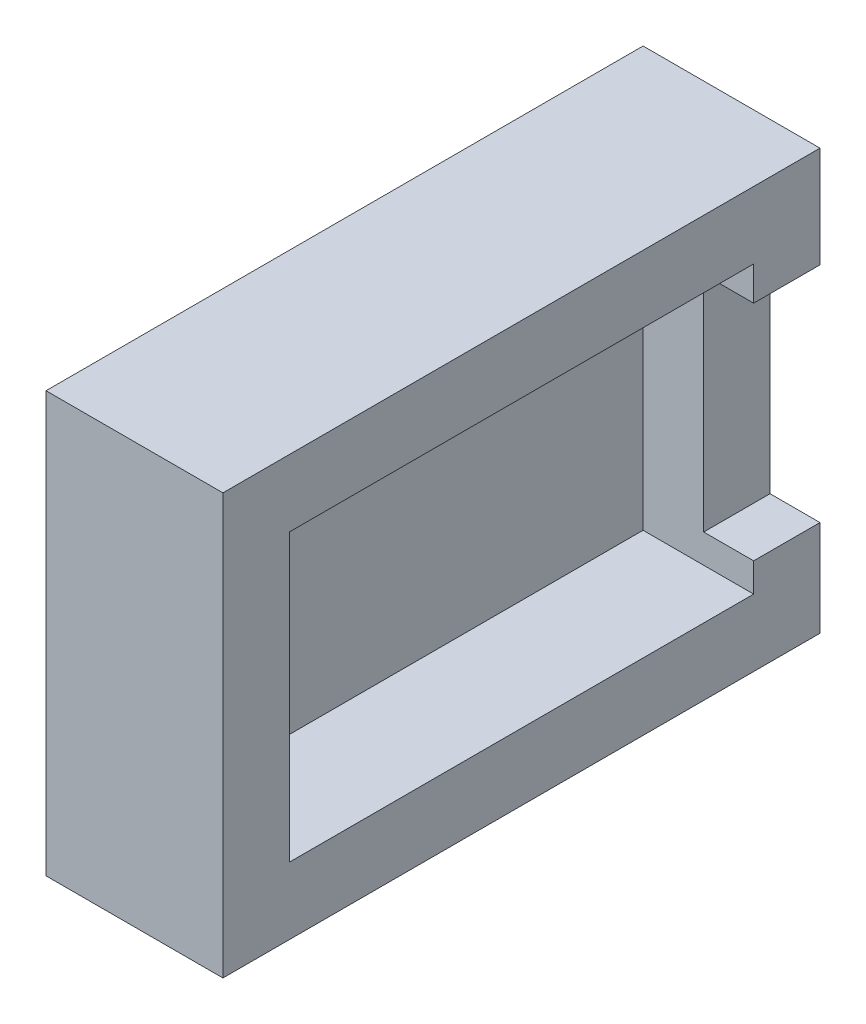
SolidWorks part; units mm, degrees
ref_plane "Front Plane" through (0, 0, 0) normal (0, 0, 1) x (1, 0, 0)
ref_plane "Top Plane" through (0, 0, 0) normal (0, 1, 0) x (1, 0, 0)
ref_plane "Right Plane" through (0, 0, 0) normal (1, 0, 0) x (0, 0, -1)
sketch "Sketch1" plane through (0, 0, 0) normal (1, 0, 0) x (0, 0, -1)
  line L1 (-13.5, 9.5) -> (13.5, 9.5)
  line L2 (-13.5, 9.5) -> (-13.5, -9.5)
  line L3 (-13.5, -9.5) -> (13.5, -9.5)
  line L4 (13.5, 9.5) -> (13.5, -9.5)
  line L5 (-13.5, 9.5) -> (13.5, -9.5) construction
  line L6 (-13.5, -9.5) -> (13.5, 9.5) construction
  point P0 (0, 0)
extrude "Boss-Extrude1" add sketch "Sketch1" along normal blind 3
sketch "Sketch2" plane through (3, 0, 0) normal (1, 0, 0) x (0, 0, -1)
  line L1 (10.5, 6.4659) -> (-10.5, 6.4659)
  line L2 (10.5, 6.4659) -> (10.5, -6.4659)
  line L3 (10.5, -6.4659) -> (-10.5, -6.4659)
  line L4 (-10.5, 6.4659) -> (-10.5, -6.4659)
  line L5 (10.5, 6.4659) -> (-10.5, -6.4659) construction
  line L6 (10.5, -6.4659) -> (-10.5, 6.4659) construction
  line L8 (13.5, -9.5) -> (-13.5, -9.5)
  line L9 (13.5, -9.5) -> (13.5, 9.5)
  line L10 (13.5, 9.5) -> (-13.5, 9.5)
  line L11 (-13.5, -9.5) -> (-13.5, 9.5)
  line L12 (13.5, -9.5) -> (-13.5, 9.5) construction
  line L13 (13.5, 9.5) -> (-13.5, -9.5) construction
  point P0 (0, 0)
  point P6 (0, 0)
extrude "Boss-Extrude2" add sketch "Sketch2" along normal blind 5
sketch "Sketch3" plane through (0, 0, -13.5) normal (0, 0, -1) x (-1, 0, 0)
  line L0 (-8, -9.5) -> (-8, 9.5) construction
  line L1 (-8, 4.9285) -> (-5.7417, 4.9285)
  line L2 (-8, 4.9285) -> (-8, -5.1627)
  line L3 (-8, -5.1627) -> (-5.7417, -5.1627)
  line L4 (-5.7417, 4.9285) -> (-5.7417, -5.1627)
extrude "Cut-Extrude1" cut sketch "Sketch3" against normal blind 3
